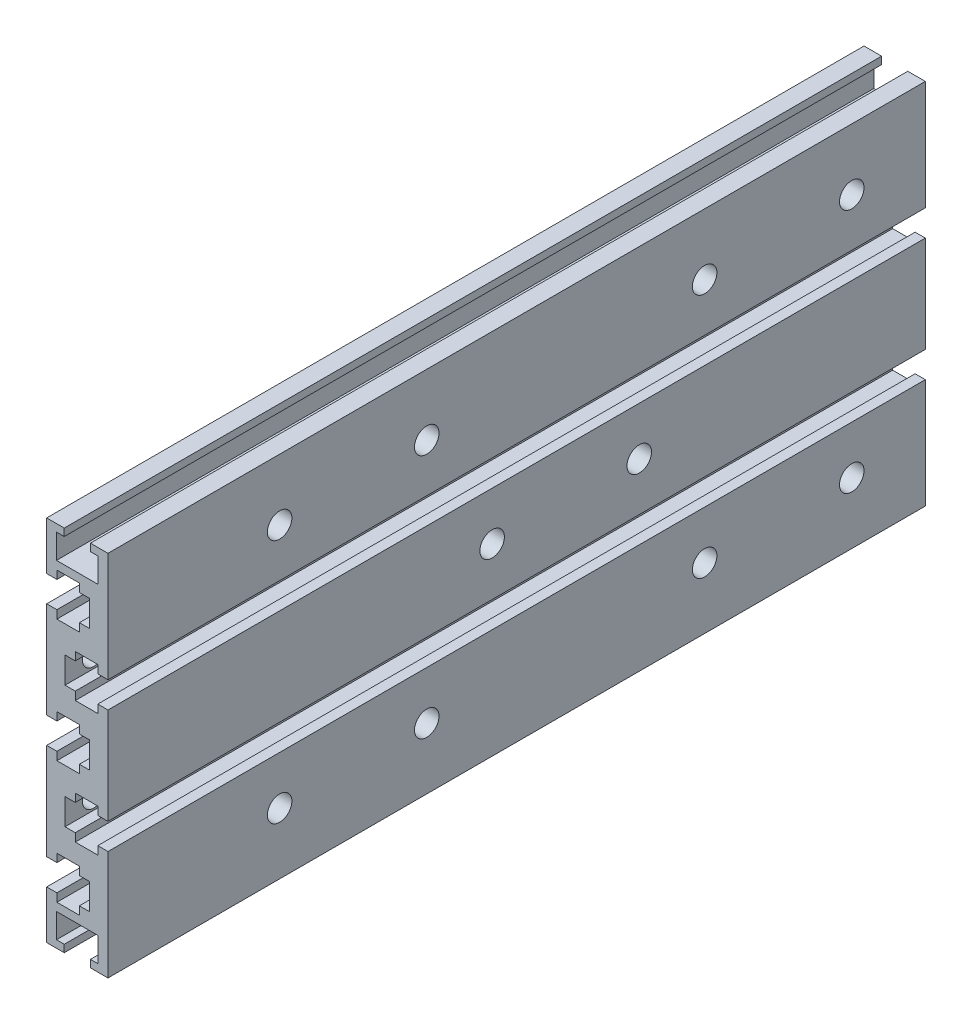
SolidWorks part; units mm, degrees
ref_plane "Plane1" through (0, 0, 0) normal (0, 0, 1) x (1, 0, 0)
ref_plane "Plane2" through (0, 0, 0) normal (0, 1, 0) x (1, 0, 0)
ref_plane "Plane3" through (0, 0, 0) normal (1, 0, 0) x (0, 0, -1)
sketch "Sketch1" plane through (0, 0, 0) normal (0, 0, 1) x (1, 0, 0)
  line L0 (0, 0) -> (75.649, 0) construction
  line L1 (-6.5, 45) -> (-3.2, 45)
  line L2 (-7.5, 44) -> (-7.5, 33.2)
  line L3 (-6.4967, -45) -> (-3.2, -45)
  line L4 (7.5, 44) -> (7.5, 18.2)
  line L5 (0, 3.6903) -> (0, 44.6054) construction
  line L6 (-3.2, 45) -> (-3.2, 43.2)
  line L7 (-3.2, 43.2) -> (-5.1, 43.2)
  line L8 (-5.1, 43.2) -> (-5.1, 37.2)
  line L9 (-5.1, 37.2) -> (5.1, 37.2)
  line L10 (5.1, 37.2) -> (5.1, 43.2)
  line L11 (5.1, 43.2) -> (3.2, 43.2)
  line L12 (3.2, 43.2) -> (3.2, 45)
  line L13 (3.2, 45) -> (6.5, 45)
  line L14 (3.2, -43.2) -> (3.2, -45)
  line L15 (5.1, -43.2) -> (3.2, -43.2)
  line L16 (5.1, -37.2) -> (5.1, -43.2)
  line L17 (-5.1, -37.2) -> (5.1, -37.2)
  line L18 (-5.1, -43.2) -> (-5.1, -37.2)
  line L19 (-3.2, -43.2) -> (-5.1, -43.2)
  line L20 (-3.2, -45) -> (-3.2, -43.2)
  line L21 (3.2, -45) -> (6.5, -45)
  line L22 (-5, -5.2) -> (0.5, -5.2)
  line L23 (-7.5, -3.2) -> (-5, -3.2)
  line L24 (-5, 3.2) -> (-7.5, 3.2)
  line L25 (0.5, -5.2) -> (0.5, -3.2)
  line L26 (-5, -3.2) -> (-5, -5.2)
  line L27 (0.5, 5.2) -> (-5, 5.2)
  line L28 (-17.4711, 15) -> (26.2798, 15) construction
  line L29 (-5, 5.2) -> (-5, 3.2)
  line L30 (-17.4711, -15) -> (26.2798, -15) construction
  line L31 (-3, -11.8) -> (-3, -18.2)
  line L32 (-0.5, -20.2) -> (-0.5, -18.2)
  line L33 (5, -11.8) -> (7.5, -11.8)
  line L34 (5, -18.2) -> (5, -20.2)
  line L35 (-0.5, -11.8) -> (-0.5, -9.8)
  line L36 (0.5, 3.2) -> (3, 3.2)
  line L37 (3, 3.2) -> (3, -3.2)
  line L38 (3, -3.2) -> (0.5, -3.2)
  line L39 (0.5, 3.2) -> (0.5, 5.2)
  line L40 (-7.5, -3.2) -> (-7.5, -26.8)
  line L41 (5, 9.8) -> (5, 11.8)
  line L42 (5, 20.2) -> (-0.5, 20.2)
  line L43 (-0.5, 9.8) -> (5, 9.8)
  line L44 (-3, 18.2) -> (-0.5, 18.2)
  line L45 (7.5, 18.2) -> (5, 18.2)
  line L46 (-0.5, 11.8) -> (-3, 11.8)
  line L47 (-0.5, 11.8) -> (-0.5, 9.8)
  line L48 (5, 18.2) -> (5, 20.2)
  line L49 (-0.5, -11.8) -> (-3, -11.8)
  line L50 (5, 11.8) -> (7.5, 11.8)
  line L51 (-0.5, 20.2) -> (-0.5, 18.2)
  line L52 (7.5, -18.2) -> (5, -18.2)
  line L53 (-3, 11.8) -> (-3, 18.2)
  line L54 (-3, -18.2) -> (-0.5, -18.2)
  line L55 (-0.5, -9.8) -> (5, -9.8)
  line L56 (5, -20.2) -> (-0.5, -20.2)
  line L57 (5, -9.8) -> (5, -11.8)
  line L58 (7.5, 11.8) -> (7.5, -11.8)
  line L59 (7.5, -18.2) -> (7.5, -44)
  line L60 (-6.5, 45) -> (-7.5, 45)
  line L61 (-7.5, 45) -> (-7.5, 44)
  line L62 (7.5, 44) -> (7.5, 45)
  line L63 (7.5, 45) -> (6.5, 45)
  line L64 (-7.5, -44) -> (-7.5, -45)
  line L65 (-7.5, -45) -> (-6.4967, -45)
  line L66 (6.5, -45) -> (7.5, -45)
  line L67 (7.5, -45) -> (7.5, -44)
  line L68 (-7.5, -26.8) -> (-5, -26.8)
  line L69 (-5, -33.2) -> (-7.5, -33.2)
  line L70 (0.5, -33.2) -> (0.5, -35.2)
  line L71 (3, -26.8) -> (0.5, -26.8)
  line L72 (3, -33.2) -> (3, -26.8)
  line L73 (0.5, -33.2) -> (3, -33.2)
  line L74 (-5, -35.2) -> (-5, -33.2)
  line L75 (0.5, -35.2) -> (-5, -35.2)
  line L76 (-5, -26.8) -> (-5, -24.8)
  line L77 (0.5, -24.8) -> (0.5, -26.8)
  line L78 (-5, -24.8) -> (0.5, -24.8)
  line L79 (-7.5, -33.2) -> (-7.5, -44)
  line L80 (-7.5, 33.2) -> (-5, 33.2)
  line L81 (-5, 26.8) -> (-7.5, 26.8)
  line L82 (0.5, 26.8) -> (0.5, 24.8)
  line L83 (3, 33.2) -> (0.5, 33.2)
  line L84 (3, 26.8) -> (3, 33.2)
  line L85 (0.5, 26.8) -> (3, 26.8)
  line L86 (-5, 24.8) -> (-5, 26.8)
  line L87 (0.5, 24.8) -> (-5, 24.8)
  line L88 (-5, 33.2) -> (-5, 35.2)
  line L89 (0.5, 35.2) -> (0.5, 33.2)
  line L90 (-5, 35.2) -> (0.5, 35.2)
  line L91 (-7.5, 26.8) -> (-7.5, 3.2)
  point P72 (-7.5, 45)
  point P73 (7.5, 45)
  point P74 (0, 45)
  point P75 (-7.5, -45)
  point P76 (7.5, -45)
  point P77 (0, -45)
  point P78 (7.5, -15)
  point P79 (-7.5, 0)
  point P80 (7.5, 15)
  point P81 (-7.5, 15)
  point P82 (7.5, 0)
  point P83 (-7.5, -15)
extrude "凸台-拉伸1" add sketch "Sketch1" along normal blind 200
ref_plane "基准面1" through (7.5, 45, 200) normal (-1, 0, 0) x (0, 0, 1)
ref_plane "基准面2" through (-7.5, 45, 200) normal (-1, 0, 0) x (0, 0, 1)
hole_wizard "Ø6.0 (6) 直径孔6" positions "草图11" profile "草图10" hole size "Ø6.0" standard "Gb" end condition through all
sketch "草图11" plane through (7.5, 0, 0) normal (1, 0, 0) x (0, 0, -1)
  line L0 (-200, -45) -> (0, -45) construction
  line L2 (0, -45) -> (0, -18.2) construction
  line L3 (0, -11.8) -> (0, 11.8) construction
  line L4 (-200, 45) -> (0, 45) construction
  point P0 (-158, -30)
  point P2 (-158, 30)
  point P4 (-122, -30)
  point P6 (-122, 30)
  point P8 (-54, 30)
  point P10 (-54, -30)
  point P12 (-18, -30)
  point P14 (-18, 30)
  point P16 (-106, 0)
  point P18 (-70, 0)
  dimension "D1" = 15
  dimension "D2" = 158
  dimension "D3" = 122
  dimension "D4" = 106
  dimension "D5" = 70
  dimension "D6" = 54
  dimension "D7" = 18
  dimension "D8" = 45
  dimension "D9" = 15
sketch "草图10" plane through (7.5, -30, 158) normal (0, 1, 0) x (0, 0, -1)
  line L0 (0, 0) -> (0, 15)
  line L1 (0, 15) -> (3, 15)
  line L2 (3, 15) -> (3, 0)
  line L5 (3, 0) -> (0, 0)
  line L11 (0, -6.35) -> (0, 107.95) construction
  dimension "通孔孔直径" = 6
  dimension "通孔孔深度" = 15
hole_wizard "Ø5.5 (5.5) 直径孔1" positions "草图13" profile "草图12" hole size "Ø5.5" standard "Gb" end condition through all
sketch "草图13" plane through (-3, 0, 0) normal (1, 0, 0) x (0, 0, -1)
  line L0 (-200, -45) -> (0, -45) construction
  line L1 (-200, 45) -> (0, 45) construction
  line L2 (-200, -45) -> (-200, -18.2) construction
  line L3 (0, -18.2) -> (0, -11.8) construction
  point P0 (-193, -15)
  point P2 (-193, 15)
  point P4 (-7, -15)
  point P6 (-7, 15)
  dimension "D1" = 30
  dimension "D2" = 30
  dimension "D3" = 7
  dimension "D4" = 7
sketch "草图12" plane through (-3, -15, 193) normal (0, 1, 0) x (0, 0, -1)
  line L0 (0, 0) -> (0, 4.5)
  line L1 (0, 4.5) -> (2.75, 4.5)
  line L2 (2.75, 4.5) -> (2.75, 0)
  line L5 (2.75, 0) -> (0, 0)
  line L11 (0, -6.35) -> (0, 107.95) construction
  dimension "通孔孔直径" = 5.5
  dimension "通孔孔深度" = 4.5
